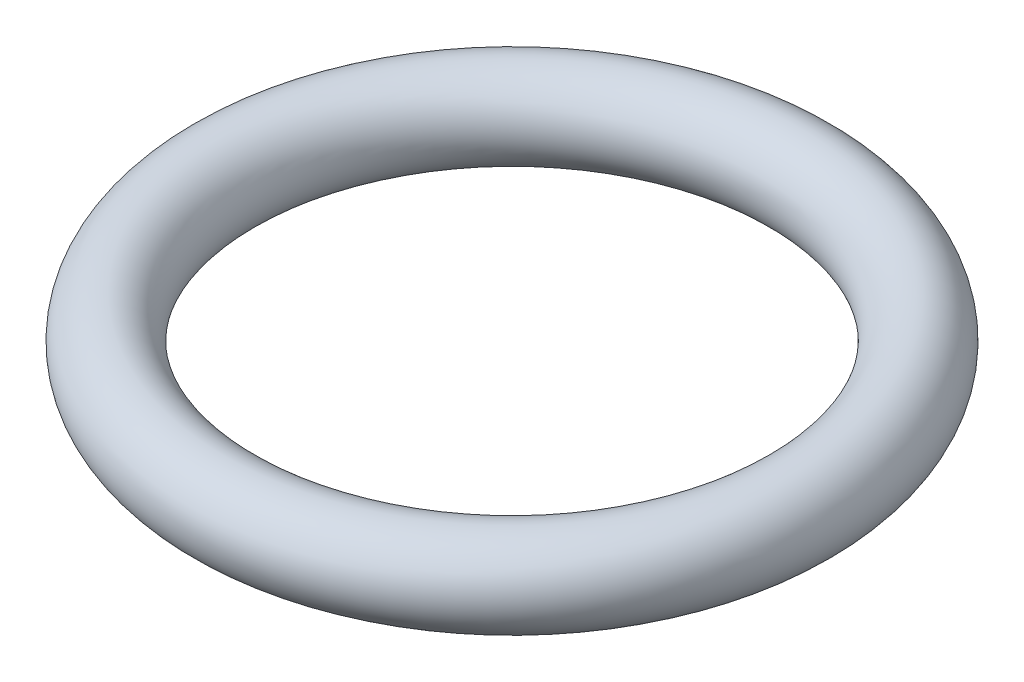
SolidWorks part; units mm, degrees
ref_plane "Front Plane" through (0, 0, 0) normal (0, 0, 1) x (1, 0, 0)
ref_plane "Top Plane" through (0, 0, 0) normal (0, 1, 0) x (1, 0, 0)
ref_plane "Right Plane" through (0, 0, 0) normal (1, 0, 0) x (0, 0, -1)
sketch "Sketch1" plane through (0, 0, 0) normal (0, 0, 1) x (1, 0, 0)
  line L0 (0, -146.1287) -> (0, 7160.3059) construction
  circle A0 centre (5.3848, 0) radius 0.7938
  point P5 (0, 0)
  dimension "D2" = 1.5875
  dimension "D1" = 5.3848
revolve "Revolve1" add sketch "Sketch1" angle 360 about L0
